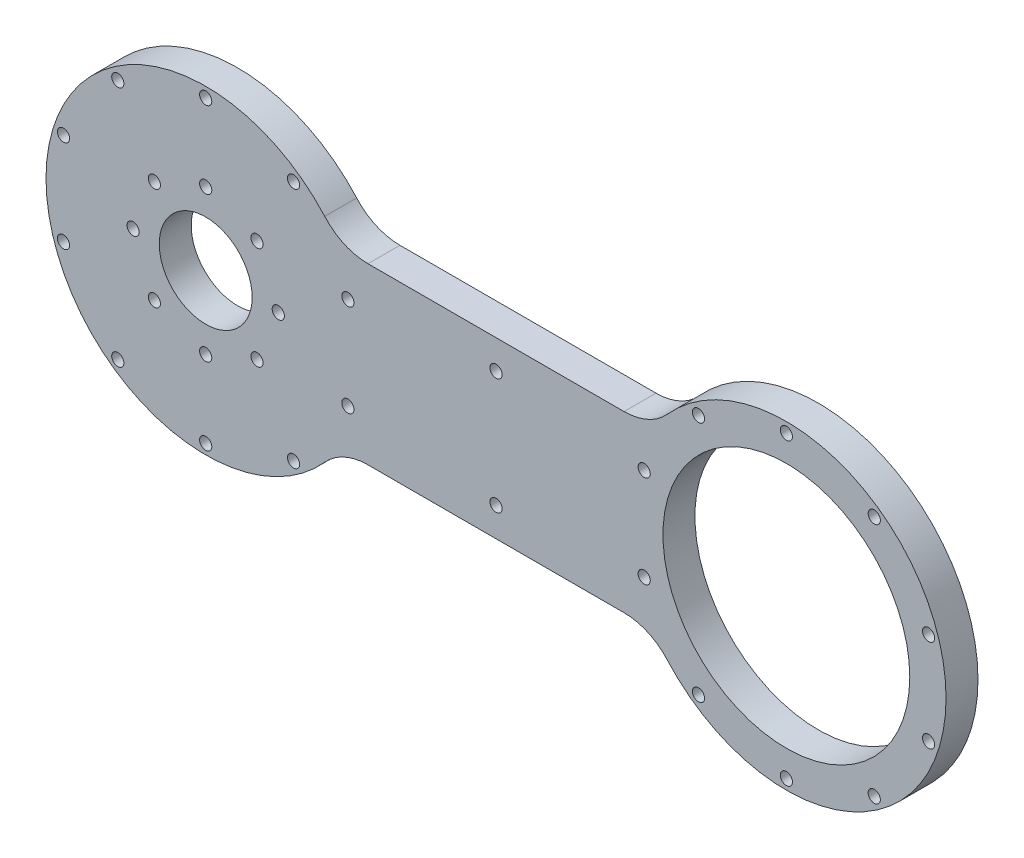
SolidWorks part; units mm, degrees
material "Delrin 2700 NC010, copolymère d'acétal à faible viscosité (SS)"
ref_plane "Plan de face" through (0, 0, 0) normal (0, 0, 1) x (1, 0, 0)
ref_plane "Plan de dessus" through (0, 0, 0) normal (0, 1, 0) x (1, 0, 0)
ref_plane "Plan de droite" through (0, 0, 0) normal (1, 0, 0) x (0, 0, -1)
sketch "Esquisse1" plane through (0, 0, 0) normal (0, 0, 1) x (1, 0, 0)
  line L0 (0, 0) -> (-200, 0) construction
  line L2 (60, 60) -> (-260, 60)
  line L3 (60, 60) -> (60, -60)
  line L4 (60, -60) -> (-260, -60)
  line L5 (-260, 60) -> (-260, -60)
  line L6 (60, 60) -> (-260, -60) construction
  line L7 (60, -60) -> (-260, 60) construction
  circle A0 centre (0, 0) radius 42.5
  circle A1 centre (-200, 0) radius 16
  point P5 (-100, 0)
  dimension "D1" = 85
  dimension "D2" = 32
  dimension "D3" = 200
  dimension "D4" = 120
  dimension "D5" = 320
extrude "Boss.-Extru.1" add sketch "Esquisse1" along normal blind 11
sketch "Esquisse2" plane through (0, 0, 11) normal (0, 0, 1) x (1, 0, 0)
  circle A0 centre (-200, 0) radius 25 construction
  circle A1 centre (-200, 25) radius 2.1
  circle A2 centre (-182.3223, 17.6777) radius 2.1
  circle A3 centre (-175, 0) radius 2.1
  circle A4 centre (-182.3223, -17.6777) radius 2.1
  circle A5 centre (-200, -25) radius 2.1
  circle A6 centre (-217.6777, -17.6777) radius 2.1
  circle A7 centre (-225, 0) radius 2.1
  circle A8 centre (-217.6777, 17.6777) radius 2.1
  point P21 (-200, 0)
  dimension "D1" = 50
  dimension "D2" = 4.2
  dimension "D3" = 8
extrude "Enlèv. mat.-Extru.1" cut sketch "Esquisse2" against normal through all
sketch "Esquisse3" plane through (0, 0, 11) normal (0, 0, 1) x (1, 0, 0)
  line L0 (-200, 0) -> (0, 0) construction
  line L1 (-200, 30) -> (0, 30) construction
  line L2 (-200, -30) -> (0, -30) construction
  line L3 (-153.9023, 30) -> (-46.0977, 30)
  line L4 (-153.9023, -30) -> (-46.0977, -30)
  circle A0 centre (-200, 0) radius 55 construction
  circle A1 centre (0, 0) radius 55 construction
  arc A2 (-200, 30) -> (-200, -30) centre (-200, 0) ccw construction
  arc A3 (0, -30) -> (0, 30) centre (0, 0) ccw construction
  arc A4 (-153.9023, 30) -> (-153.9023, -30) centre (-200, 0) ccw
  arc A5 (-46.0977, 30) -> (-46.0977, -30) centre (0, 0) cw
  point P6 (-100, 0)
  point P14 (-160, -30)
  point P16 (-40, -30)
  point P18 (-40, 30)
  point P20 (-160, 30)
  point P22 (0, 0)
  point P23 (-160, -30)
  point P24 (-160, -30)
  dimension "D1" = 110
  dimension "D2" = 110
  dimension "D3" = 60
extrude "Enlèv. mat.-Extru.2" cut sketch "Esquisse3" against normal through all flip side to cut
fillet "Congé1" radius 20 4 edges at (-153.9023, -30, 5.5) (-46.0977, -30, 5.5) (-46.0977, 30, 5.5) (-153.9023, 30, 5.5)
sketch "Esquisse4" plane through (0, 0, 11) normal (0, 0, 1) x (1, 0, 0)
  line L0 (-100, 30) -> (-100, -30) construction
  line L1 (-55.9017, 30) -> (-144.0983, 30) construction
  line L2 (-144.0983, -30) -> (-55.9017, -30) construction
  circle A0 centre (-200, 0) radius 51.5 construction
  circle A1 centre (-200, 51.5) radius 2.1
  circle A2 centre (-169.7291, 41.6644) radius 2.1
  circle A3 centre (-151.0206, 15.9144) radius 2.1
  circle A4 centre (-151.0206, -15.9144) radius 2.1
  circle A5 centre (-169.7291, -41.6644) radius 2.1
  circle A6 centre (-200, -51.5) radius 2.1
  circle A7 centre (-230.2709, -41.6644) radius 2.1
  circle A8 centre (-248.9794, -15.9144) radius 2.1
  circle A9 centre (-248.9794, 15.9144) radius 2.1
  circle A10 centre (-230.2709, 41.6644) radius 2.1
  circle A11 centre (0, 0) radius 51.5 construction
  circle A12 centre (30.2709, 41.6644) radius 2.1
  circle A13 centre (48.9794, 15.9144) radius 2.1
  circle A14 centre (48.9794, -15.9144) radius 2.1
  circle A15 centre (30.2709, -41.6644) radius 2.1
  circle A16 centre (0, -51.5) radius 2.1
  circle A17 centre (-30.2709, -41.6644) radius 2.1
  circle A18 centre (-48.9794, -15.9144) radius 2.1
  circle A19 centre (-48.9794, 15.9144) radius 2.1
  circle A20 centre (-30.2709, 41.6644) radius 2.1
  circle A21 centre (0, 51.5) radius 2.1
  point P25 (-200, 0)
  dimension "D1" = 103
  dimension "D2" = 4.2
  dimension "D3" = 10
extrude "Enlèv. mat.-Extru.3" cut sketch "Esquisse4" against normal through all
sketch "Esquisse5" plane through (0, 0, 11) normal (0, 0, 1) x (1, 0, 0)
  line L0 (-100, 30) -> (-100, -30) construction
  line L1 (-55.9017, 30) -> (-144.0983, 30) construction
  line L2 (-144.0983, -30) -> (-55.9017, -30) construction
  circle A0 centre (-100, 20) radius 2.1
  circle A1 centre (-100, -20) radius 2.1
  dimension "D1" = 4.2
  dimension "D3" = 4.2
  dimension "D2" = 10
  dimension "D4" = 10
extrude "Enlèv. mat.-Extru.4" cut sketch "Esquisse5" against normal blind 84
